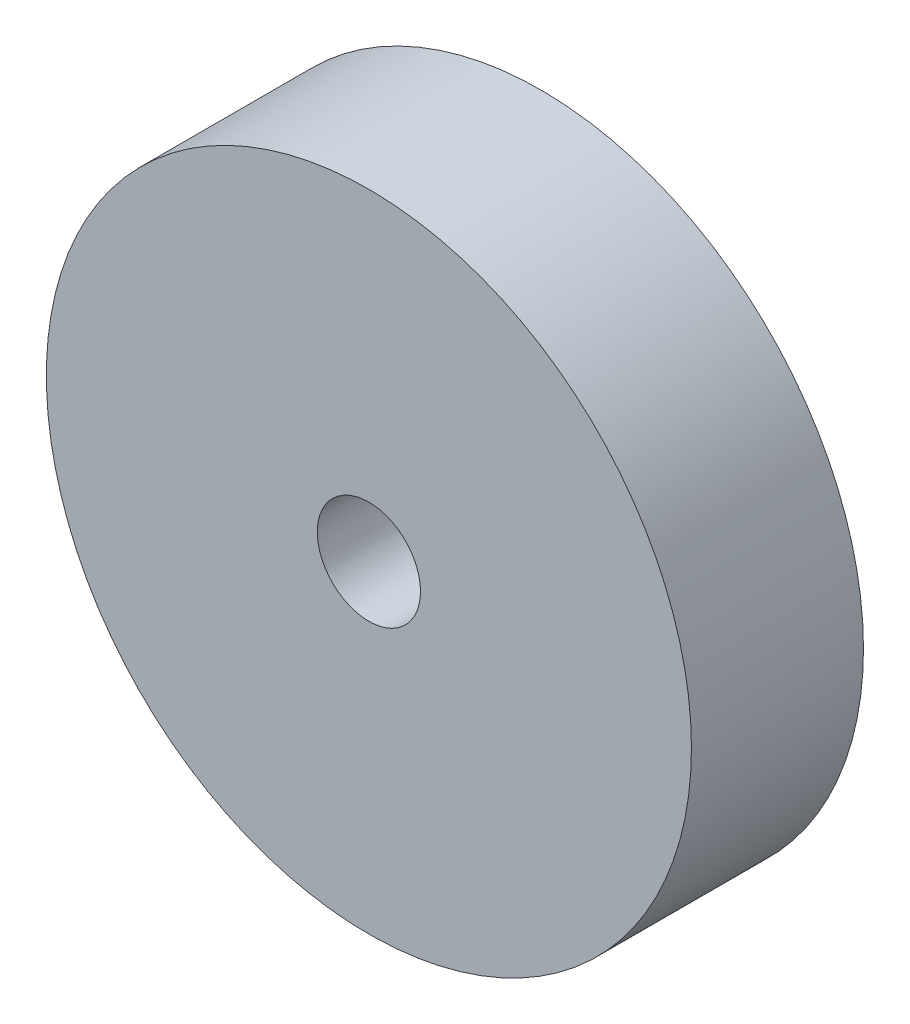
SolidWorks part; units mm, degrees
ref_plane "Płaszczyzna przednia" through (0, 0, 0) normal (0, 0, 1) x (1, 0, 0)
ref_plane "Płaszczyzna górna" through (0, 0, 0) normal (0, 1, 0) x (1, 0, 0)
ref_plane "Płaszczyzna prawa" through (0, 0, 0) normal (1, 0, 0) x (0, 0, -1)
sketch "Szkic1" plane through (0, 0, 0) normal (0, 0, 1) x (1, 0, 0)
  circle A0 centre (0, 0) radius 37.5
  circle A1 centre (0, 0) radius 6
  dimension "D1" = 75
  dimension "D2" = 12
extrude "Dodanie-wyciągnięcie1" add sketch "Szkic1" along normal mid plane 20
